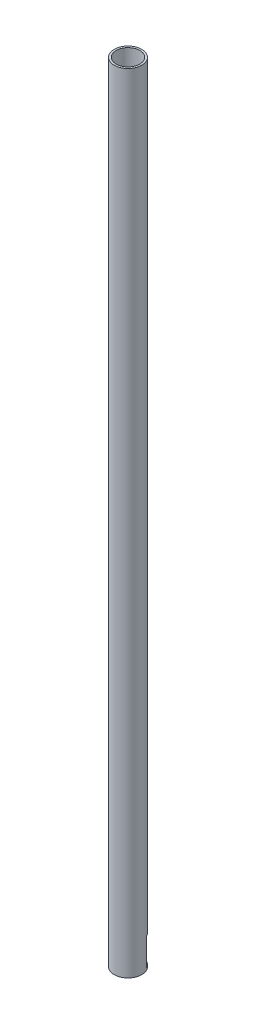
SolidWorks part; units mm, degrees
material "1060 Alloy"
ref_plane "Front Plane" through (0, 0, 0) normal (0, 0, 1) x (1, 0, 0)
ref_plane "Top Plane" through (0, 0, 0) normal (0, 1, 0) x (1, 0, 0)
ref_plane "Right Plane" through (0, 0, 0) normal (1, 0, 0) x (0, 0, -1)
sketch "Sketch1" plane through (0, 0, 0) normal (0, 1, 0) x (1, 0, 0)
  circle A0 centre (0, 0) radius 7
  circle A1 centre (0, 0) radius 6
extrude "Boss-Extrude1" add sketch "Sketch1" along normal blind 400
ref_plane "Plane1" through (0, 0, -10) normal (0, 0, 1) x (1, 0, 0)
sketch "Sketch3" plane through (0, 0, -10) normal (0, 0, 1) x (1, 0, 0)
  line L0 (0, 0) -> (0, 1)
  line L1 (-7, 0) -> (7, 0) construction
  line L2 (0, 1) -> (8, 1)
  line L3 (8, 1) -> (8, 15)
  line L4 (8, 15) -> (-6, 15)
  line L5 (-6, 15) -> (-6, 1)
  line L6 (-6, 1) -> (0, 1)
extrude "Cut-Extrude1" cut sketch "Sketch3" along normal blind 7 contours L5 L6 L2 L3 L4
